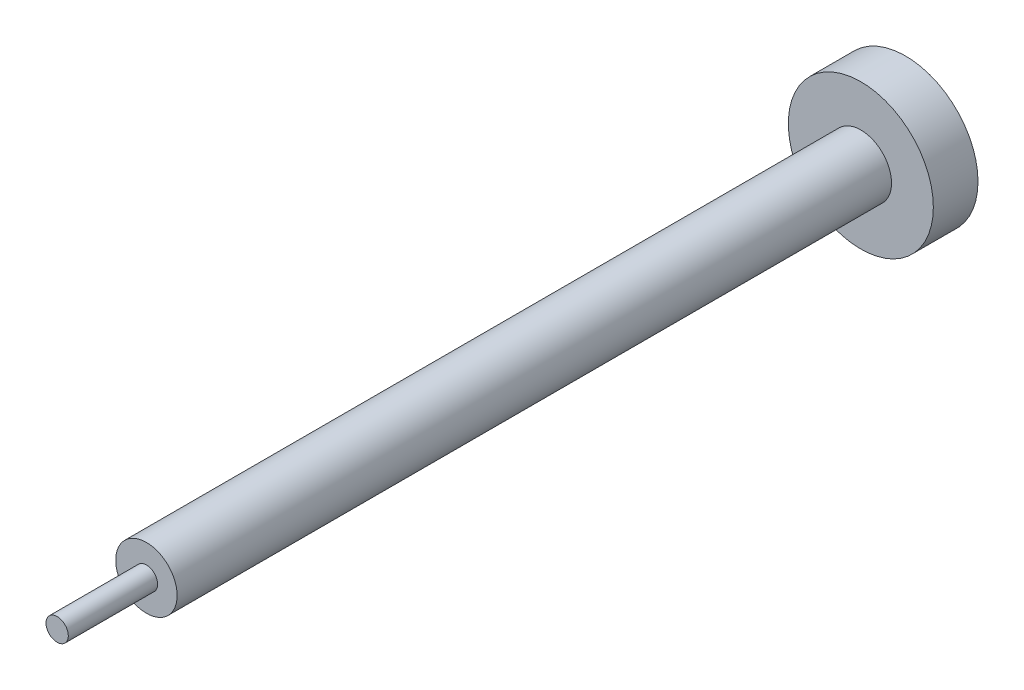
SolidWorks part; units mm, degrees
ref_plane "Front Plane" through (0, 0, 0) normal (0, 0, 1) x (1, 0, 0)
ref_plane "Top Plane" through (0, 0, 0) normal (0, 1, 0) x (1, 0, 0)
ref_plane "Right Plane" through (0, 0, 0) normal (1, 0, 0) x (0, 0, -1)
sketch "Sketch1" plane through (0, 0, 0) normal (0, 0, 1) x (1, 0, 0)
  circle A0 centre (0, 0) radius 20.6248
  dimension "D1" = 41.2496
extrude "Boss-Extrude1" add sketch "Sketch1" against normal blind 12.7
sketch "Sketch2" plane through (0, 0, 0) normal (0, 0, 1) x (1, 0, 0)
  circle A0 centre (0, 0) radius 8.7312
  dimension "D1" = 17.4625
extrude "Boss-Extrude2" add sketch "Sketch2" along normal blind 203.2
sketch "Sketch3" plane through (0, 0, 203.2) normal (0, 0, 1) x (1, 0, 0)
  circle A0 centre (0, 0) radius 3.175
  dimension "D1" = 6.35
extrude "Boss-Extrude3" add sketch "Sketch3" along normal blind 25.4
scale "Scale1" scale about centroid uniform scaling yes scale factor 0.66
